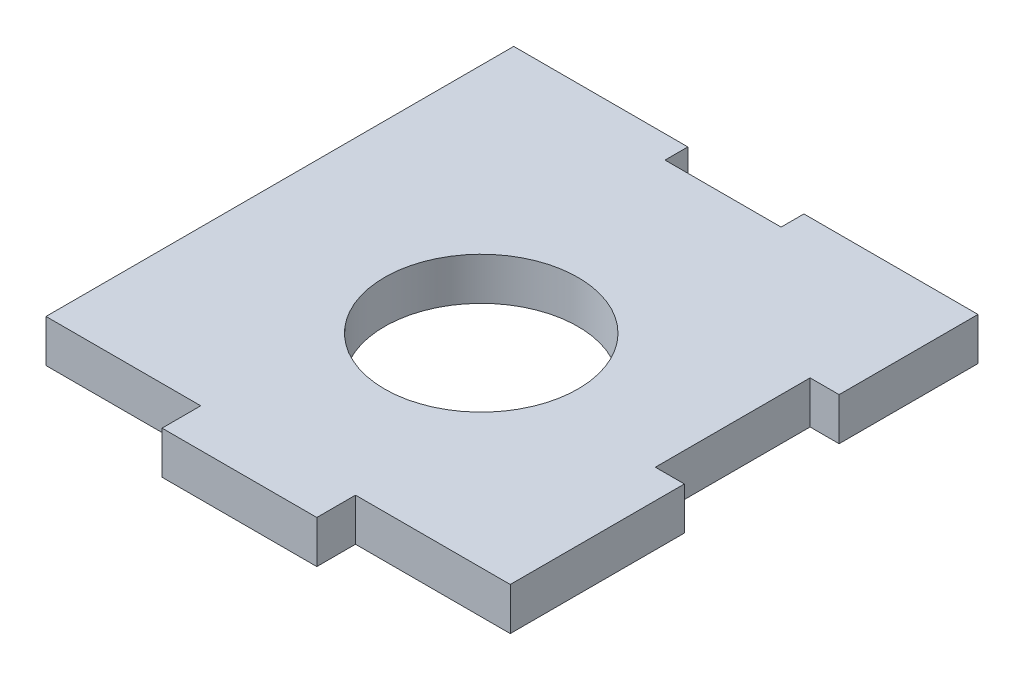
SolidWorks part; units mm, degrees
material "cardboard"
ref_plane "Front Plane" through (0, 0, 0) normal (0, 0, 1) x (1, 0, 0)
ref_plane "Top Plane" through (0, 0, 0) normal (0, 1, 0) x (1, 0, 0)
ref_plane "Right Plane" through (0, 0, 0) normal (1, 0, 0) x (0, 0, -1)
sketch "Sketch1" plane through (0, 0, 0) normal (0, 1, 0) x (1, 0, 0)
  line L0 (77.2136, 11.3295) -> (70.3635, 7.3746)
  line L1 (102.7136, -12.6705) -> (109.5638, -8.7155)
  line L2 (117.8635, 7.3746) -> (109.5638, 7.3746)
  line L3 (117.8635, -8.7155) -> (109.5638, -8.7155)
  line L4 (70.3635, 7.3746) -> (62.0638, 7.3746)
  line L5 (124.7136, 11.3295) -> (117.8635, 7.3746)
  line L6 (124.7136, -12.6705) -> (117.8635, -8.7155)
  line L7 (102.7136, 11.3295) -> (109.5638, 7.3746)
  line L8 (124.7136, 11.3295) -> (137.4636, 11.3295)
  line L9 (124.7136, -12.6705) -> (161.4636, -12.6705)
  line L10 (55.2136, 11.3295) -> (62.0638, 7.3746)
  line L11 (55.2136, -12.6705) -> (62.0638, -8.7155)
  line L12 (77.2136, -12.6705) -> (70.3635, -8.7155)
  line L13 (70.3635, -8.7155) -> (62.0638, -8.7155)
  line L14 (77.2136, 11.3295) -> (102.7136, 11.3295)
  line L15 (77.2136, -12.6705) -> (102.7136, -12.6705)
  line L16 (-12.5364, 77.0795) -> (-8.5815, 70.2294)
  line L17 (11.4636, 102.5795) -> (7.5087, 109.4297)
  line L18 (-8.5815, 117.7294) -> (-8.5815, 109.4297)
  line L19 (7.5087, 117.7294) -> (7.5087, 109.4297)
  line L20 (-8.5815, 70.2294) -> (-8.5815, 61.9297)
  line L21 (-12.5364, 124.5795) -> (-8.5815, 117.7294)
  line L22 (11.4636, 124.5795) -> (7.5087, 117.7294)
  line L23 (-12.5364, 102.5795) -> (-8.5815, 109.4297)
  line L24 (-12.5364, 124.5795) -> (-12.5364, 137.3295)
  line L25 (11.4636, 124.5795) -> (11.4636, 161.3295)
  line L26 (-12.5364, 55.0795) -> (-8.5815, 61.9297)
  line L27 (11.4636, 55.0795) -> (7.5087, 61.9297)
  line L28 (11.4636, 77.0795) -> (7.5087, 70.2294)
  line L29 (7.5087, 70.2294) -> (7.5087, 61.9297)
  line L30 (-12.5364, 77.0795) -> (-12.5364, 102.5795)
  line L31 (11.4636, 77.0795) -> (11.4636, 102.5795)
  line L32 (89.9636, 36.3295) -> (89.9636, 16.3295)
  line L33 (88.9636, 36.3295) -> (88.9636, 30.3295)
  line L34 (36.4636, 11.3295) -> (42.4636, 11.3295)
  line L35 (88.9636, 30.3295) -> (90.9636, 30.3295)
  line L36 (41.2136, 11.3295) -> (41.2136, 9.3295)
  line L37 (42.4636, 11.3295) -> (55.2136, 11.3295)
  line L38 (137.4636, 11.3295) -> (137.4636, -12.6705)
  line L39 (137.4636, 11.3295) -> (161.4636, 11.3295)
  line L40 (161.4636, 11.3295) -> (161.4636, 9.3295)
  line L41 (-29.0328, 13.6838) -> (-0.5364, -14.8126)
  line L42 (-29.0328, 13.6838) -> (-14.8907, 27.8259)
  line L43 (-0.5364, -14.8126) -> (13.6058, -0.6705)
  line L44 (-14.8907, 27.8259) -> (13.6058, -0.6705)
  line L45 (137.4636, 11.3295) -> (137.4636, 36.3295)
  line L46 (39.4636, 36.3295) -> (161.4636, 36.3295)
  line L47 (161.4636, 36.3295) -> (161.4636, 11.3295)
  line L48 (90.9636, 30.3295) -> (90.9636, 22.3295)
  line L49 (137.4636, 36.3295) -> (137.4636, 60.3295)
  line L50 (137.4636, 60.3295) -> (146.4636, 60.3295)
  line L51 (42.4636, 36.3295) -> (42.4636, 16.3295)
  line L52 (161.4636, 60.3295) -> (161.4636, 50.6515)
  line L53 (146.4636, 60.3295) -> (146.4636, 62.5295)
  line L54 (152.4636, 62.5295) -> (152.4636, 60.3295)
  line L55 (152.4636, 60.3295) -> (161.4636, 60.3295)
  line L56 (-59.5364, 137.3295) -> (-59.5364, 112.8295)
  line L57 (-39.5364, 112.8295) -> (-39.5364, 137.3295)
  line L58 (90.9636, 22.3295) -> (88.9636, 22.3295)
  line L59 (137.4636, -12.6705) -> (137.4636, -37.6705)
  line L60 (146.4636, -37.6705) -> (152.4636, -37.6705)
  line L61 (161.4636, -37.6705) -> (161.4636, -12.6705)
  line L62 (42.4636, -37.6705) -> (42.4636, -17.6705)
  line L63 (137.4636, -37.6705) -> (137.4636, -38.8505)
  line L64 (152.4636, -38.8505) -> (161.4636, -38.8505)
  line L65 (161.4636, -38.8505) -> (161.4636, -37.6705)
  line L66 (146.4636, -38.8505) -> (146.4636, -37.6705)
  line L67 (152.4636, -38.8505) -> (152.4636, -37.6705)
  line L68 (-38.7164, -138.6705) -> (-38.7164, -147.6705)
  line L69 (88.9636, 22.3295) -> (88.9636, 16.3295)
  line L70 (88.9636, 11.3295) -> (88.9636, 3.3295)
  line L71 (42.4636, -12.6705) -> (55.2136, -12.6705)
  line L72 (36.4636, -12.6705) -> (42.4636, -12.6705)
  line L73 (89.9374, 11.3295) -> (89.9374, -12.6705)
  line L74 (88.9636, 3.3295) -> (90.9636, 3.3295)
  line L75 (90.9636, 3.3295) -> (90.9636, -4.6705)
  line L76 (90.9636, -4.6705) -> (88.9636, -4.6705)
  line L77 (135.4636, 11.3295) -> (135.4636, 3.3295)
  line L78 (135.4636, 3.3295) -> (139.4636, 3.3295)
  line L79 (37.6436, 161.3295) -> (37.6436, 152.3295)
  line L80 (37.4636, 34.3295) -> (37.4636, 18.3295)
  line L81 (39.4636, 16.3295) -> (137.4636, 16.3295)
  line L82 (41.2136, 23.3295) -> (41.2136, 16.3295)
  line L83 (42.4636, 29.3295) -> (39.4636, 29.3295)
  line L84 (39.4636, 29.3295) -> (39.4636, 23.3295)
  line L85 (43.7136, 5.3295) -> (41.2136, 5.3295)
  line L86 (5.4636, -42.4205) -> (5.4636, -40.4205)
  line L87 (41.2136, -6.6705) -> (43.7136, -6.6705)
  line L88 (43.7136, 5.3295) -> (43.7136, -6.6705)
  line L89 (42.4636, 11.3295) -> (42.4636, 5.3295)
  line L90 (41.2136, 9.3295) -> (43.7136, 9.3295)
  line L91 (43.7136, 9.3295) -> (43.7136, 7.3295)
  line L92 (43.7136, 7.3295) -> (41.2136, 7.3295)
  line L93 (41.2136, 7.3295) -> (41.2136, 5.3295)
  line L94 (41.2136, -8.6705) -> (41.2136, -6.6705)
  line L95 (43.7136, -8.6705) -> (41.2136, -8.6705)
  line L96 (43.7136, -10.6705) -> (43.7136, -8.6705)
  line L97 (41.2136, -10.6705) -> (43.7136, -10.6705)
  line L98 (41.2136, -12.6705) -> (41.2136, -10.6705)
  line L99 (139.4636, 3.3295) -> (139.4636, -4.6705)
  line L100 (139.4636, -4.6705) -> (135.4636, -4.6705)
  line L101 (135.4636, -4.6705) -> (135.4636, -12.6705)
  line L102 (137.4636, 13.3295) -> (145.4636, 13.3295)
  line L103 (145.4636, 13.3295) -> (145.4636, 9.3295)
  line L104 (145.4636, 9.3295) -> (153.4636, 9.3295)
  line L105 (153.4636, 9.3295) -> (153.4636, 13.3295)
  line L106 (153.4636, 13.3295) -> (161.4636, 13.3295)
  line L107 (135.9636, 36.3295) -> (135.9636, 30.3295)
  line L108 (135.9636, 30.3295) -> (138.9636, 30.3295)
  line L109 (138.9636, 30.3295) -> (138.9636, 22.3295)
  line L110 (138.9636, 22.3295) -> (135.9636, 22.3295)
  line L111 (135.9636, 22.3295) -> (135.9636, 16.3295)
  line L112 (88.9636, -4.6705) -> (88.9636, -12.6705)
  line L113 (88.9636, -23.6705) -> (88.9636, -17.6705)
  line L114 (89.9636, -37.6705) -> (89.9636, -17.6705)
  line L115 (90.9636, -23.6705) -> (88.9636, -23.6705)
  line L116 (90.9636, -31.6705) -> (90.9636, -23.6705)
  line L117 (153.4636, -14.6705) -> (161.4636, -14.6705)
  line L118 (153.4636, -10.6705) -> (153.4636, -14.6705)
  line L119 (145.4636, -10.6705) -> (153.4636, -10.6705)
  line L120 (145.4636, -14.6705) -> (145.4636, -10.6705)
  line L121 (137.4636, -14.6705) -> (145.4636, -14.6705)
  line L122 (135.9636, -23.6705) -> (135.9636, -17.6705)
  line L123 (138.9636, -23.6705) -> (135.9636, -23.6705)
  line L124 (41.2136, 36.3295) -> (41.2136, 29.3295)
  line L125 (42.4636, 23.3295) -> (39.4636, 23.3295)
  line L126 (137.4636, -37.6705) -> (39.4636, -37.6705)
  line L127 (37.4636, -35.6705) -> (37.4636, -19.6705)
  line L128 (39.4636, -17.6705) -> (137.4636, -17.6705)
  line L129 (138.9636, -31.6705) -> (138.9636, -23.6705)
  line L130 (135.9636, -31.6705) -> (138.9636, -31.6705)
  line L131 (135.9636, -37.6705) -> (135.9636, -31.6705)
  line L132 (88.9636, -31.6705) -> (90.9636, -31.6705)
  line L133 (88.9636, -37.6705) -> (88.9636, -31.6705)
  line L134 (137.4636, 38.3295) -> (145.4636, 38.3295)
  line L135 (145.4636, 38.3295) -> (145.4636, 34.3295)
  line L136 (145.4636, 34.3295) -> (153.4636, 34.3295)
  line L137 (153.4636, 34.3295) -> (153.4636, 38.3295)
  line L138 (153.4636, 38.3295) -> (161.4636, 38.3295)
  line L139 (-45.0364, 133.0795) -> (-45.0364, 117.0795)
  line L140 (-56.5364, 133.0795) -> (-54.0364, 133.0795)
  line L141 (-56.5364, 133.0795) -> (-56.5364, 117.0795)
  line L142 (-56.5364, 117.0795) -> (-54.0364, 117.0795)
  line L143 (-54.0364, 133.0795) -> (-54.0364, 117.0795)
  line L144 (41.2136, -24.6705) -> (41.2136, -17.6705)
  line L145 (42.4636, -24.6705) -> (39.4636, -24.6705)
  line L146 (39.4636, -30.6705) -> (39.4636, -24.6705)
  line L147 (42.4636, -30.6705) -> (39.4636, -30.6705)
  line L148 (41.2136, -37.6705) -> (41.2136, -30.6705)
  line L149 (196.4636, 4.3295) -> (196.4636, -5.6705)
  line L150 (191.4636, 9.3295) -> (161.4636, 9.3295)
  line L151 (191.4636, -10.6705) -> (161.4636, -10.6705)
  line L152 (191.4636, 9.3295) -> (196.4636, 4.3295)
  line L153 (196.4636, -5.6705) -> (191.4636, -10.6705)
  line L154 (161.4636, -10.6705) -> (161.4636, -12.6705)
  line L155 (137.4636, 62.5295) -> (146.4636, 62.5295)
  line L156 (137.4636, 62.5295) -> (137.4636, 64.5295)
  line L157 (137.4636, 64.5295) -> (161.4636, 64.5295)
  line L158 (161.4636, 64.5295) -> (161.4636, 62.5295)
  line L159 (152.4636, 62.5295) -> (161.4636, 62.5295)
  line L160 (-42.5364, 117.0795) -> (-45.0364, 117.0795)
  line L161 (-42.5364, 133.0795) -> (-42.5364, 117.0795)
  line L162 (-42.5364, 133.0795) -> (-45.0364, 133.0795)
  line L163 (154.8636, 50.6515) -> (161.4636, 50.6515)
  line L164 (154.8636, 50.6515) -> (154.8636, 46.1515)
  line L165 (154.8636, 46.1515) -> (161.4636, 46.1515)
  line L166 (161.4636, 46.1515) -> (161.4636, 36.3295)
  line L167 (11.4636, -78.4205) -> (7.5087, -71.5703)
  line L168 (-12.5364, -103.9205) -> (-8.5815, -110.7706)
  line L169 (7.5087, -119.0703) -> (7.5087, -110.7706)
  line L170 (11.4636, -37.6705) -> (11.4636, -43.6705)
  line L171 (11.4636, -42.4205) -> (9.4636, -42.4205)
  line L172 (11.4636, -43.6705) -> (11.4636, -56.4205)
  line L173 (-8.5815, -119.0703) -> (-8.5815, -110.7706)
  line L174 (7.5087, -71.5703) -> (7.5087, -63.2706)
  line L175 (11.4636, -125.9205) -> (7.5087, -119.0703)
  line L176 (-12.5364, -125.9205) -> (-8.5815, -119.0703)
  line L177 (11.4636, -103.9205) -> (7.5087, -110.7706)
  line L178 (11.4636, -125.9205) -> (11.4636, -138.6705)
  line L179 (-12.5364, -125.9205) -> (-12.5364, -162.6705)
  line L180 (11.4636, -56.4205) -> (7.5087, -63.2706)
  line L181 (-12.5364, -56.4205) -> (-8.5815, -63.2706)
  line L182 (36.4636, -43.6705) -> (16.4636, -43.6705)
  line L183 (-12.5364, -78.4205) -> (-8.5815, -71.5703)
  line L184 (-8.5815, -71.5703) -> (-8.5815, -63.2706)
  line L185 (11.4636, -78.4205) -> (11.4636, -103.9205)
  line L186 (-12.5364, -78.4205) -> (-12.5364, -103.9205)
  line L187 (36.4636, -91.1705) -> (16.4636, -91.1705)
  line L188 (36.4636, -90.1705) -> (30.4636, -90.1705)
  line L189 (30.4636, -90.1705) -> (30.4636, -92.1705)
  line L190 (11.4636, -138.6705) -> (-12.5364, -138.6705)
  line L191 (11.4636, -138.6705) -> (11.4636, -162.6705)
  line L192 (11.4636, -162.6705) -> (9.4636, -162.6705)
  line L193 (11.4636, -138.6705) -> (36.4636, -138.6705)
  line L194 (36.4636, -40.6705) -> (36.4636, -162.6705)
  line L195 (-37.5364, -43.6705) -> (-17.5364, -43.6705)
  line L196 (36.4636, -162.6705) -> (11.4636, -162.6705)
  line L197 (30.4636, -92.1705) -> (22.4636, -92.1705)
  line L198 (36.4636, -138.6705) -> (60.4636, -138.6705)
  line L199 (60.4636, -138.6705) -> (60.4636, -147.6705)
  line L200 (60.4636, -162.6705) -> (50.7856, -162.6705)
  line L201 (60.4636, -147.6705) -> (62.6636, -147.6705)
  line L202 (62.6636, -153.6705) -> (60.4636, -153.6705)
  line L203 (60.4636, -153.6705) -> (60.4636, -162.6705)
  line L204 (-12.5364, -43.6705) -> (-12.5364, -56.4205)
  line L205 (-12.5364, -37.6705) -> (-12.5364, -43.6705)
  line L206 (22.4636, -92.1705) -> (22.4636, -90.1705)
  line L207 (-12.5364, -138.6705) -> (-37.5364, -138.6705)
  line L208 (-37.5364, -147.6705) -> (-37.5364, -153.6705)
  line L209 (37.6436, 146.3295) -> (37.6436, 137.3295)
  line L210 (34.4636, -38.6705) -> (18.4636, -38.6705)
  line L211 (16.4636, -40.6705) -> (16.4636, -138.6705)
  line L212 (23.4636, -42.4205) -> (16.4636, -42.4205)
  line L213 (29.4636, -43.6705) -> (29.4636, -40.6705)
  line L214 (29.4636, -40.6705) -> (23.4636, -40.6705)
  line L215 (5.4636, -44.9205) -> (5.4636, -42.4205)
  line L216 (-37.5364, -162.6705) -> (-12.5364, -162.6705)
  line L217 (-6.5364, -42.4205) -> (-6.5364, -44.9205)
  line L218 (5.4636, -44.9205) -> (-6.5364, -44.9205)
  line L219 (11.4636, -43.6705) -> (5.4636, -43.6705)
  line L220 (9.4636, -42.4205) -> (9.4636, -44.9205)
  line L221 (9.4636, -44.9205) -> (7.4636, -44.9205)
  line L222 (7.4636, -44.9205) -> (7.4636, -42.4205)
  line L223 (7.4636, -42.4205) -> (5.4636, -42.4205)
  line L224 (-8.5364, -42.4205) -> (-6.5364, -42.4205)
  line L225 (-8.5364, -44.9205) -> (-8.5364, -42.4205)
  line L226 (-10.5364, -44.9205) -> (-8.5364, -44.9205)
  line L227 (-10.5364, -42.4205) -> (-10.5364, -44.9205)
  line L228 (-12.5364, -42.4205) -> (-10.5364, -42.4205)
  line L229 (-37.5364, -138.6705) -> (-38.7164, -138.6705)
  line L230 (-38.7164, -153.6705) -> (-38.7164, -162.6705)
  line L231 (-38.7164, -162.6705) -> (-37.5364, -162.6705)
  line L232 (-38.7164, -147.6705) -> (-37.5364, -147.6705)
  line L233 (-38.7164, -153.6705) -> (-37.5364, -153.6705)
  line L234 (-162.5364, 37.5095) -> (-153.5364, 37.5095)
  line L235 (22.4636, -90.1705) -> (16.4636, -90.1705)
  line L236 (11.4636, -90.1705) -> (3.4636, -90.1705)
  line L237 (11.4636, -91.1443) -> (-12.5364, -91.1443)
  line L238 (3.4636, -90.1705) -> (3.4636, -92.1705)
  line L239 (3.4636, -92.1705) -> (-4.5364, -92.1705)
  line L240 (-4.5364, -92.1705) -> (-4.5364, -90.1705)
  line L241 (11.4636, -136.6705) -> (3.4636, -136.6705)
  line L242 (3.4636, -136.6705) -> (3.4636, -140.6705)
  line L243 (3.4636, -140.6705) -> (-4.5364, -140.6705)
  line L244 (-4.5364, -140.6705) -> (-4.5364, -136.6705)
  line L245 (-4.5364, -136.6705) -> (-12.5364, -136.6705)
  line L246 (13.4636, -138.6705) -> (13.4636, -146.6705)
  line L247 (13.4636, -146.6705) -> (9.4636, -146.6705)
  line L248 (9.4636, -146.6705) -> (9.4636, -154.6705)
  line L249 (9.4636, -154.6705) -> (13.4636, -154.6705)
  line L250 (13.4636, -154.6705) -> (13.4636, -162.6705)
  line L251 (36.4636, -137.1705) -> (30.4636, -137.1705)
  line L252 (30.4636, -137.1705) -> (30.4636, -140.1705)
  line L253 (30.4636, -140.1705) -> (22.4636, -140.1705)
  line L254 (36.4636, -42.4205) -> (29.4636, -42.4205)
  line L255 (23.4636, -43.6705) -> (23.4636, -40.6705)
  line L256 (-37.5364, -138.6705) -> (-37.5364, -40.6705)
  line L257 (-35.5364, -38.6705) -> (-19.5364, -38.6705)
  line L258 (-17.5364, -40.6705) -> (-17.5364, -138.6705)
  line L259 (22.4636, -140.1705) -> (22.4636, -137.1705)
  line L260 (22.4636, -137.1705) -> (16.4636, -137.1705)
  line L261 (-4.5364, -90.1705) -> (-12.5364, -90.1705)
  line L262 (-23.5364, -90.1705) -> (-17.5364, -90.1705)
  line L263 (-37.5364, -91.1705) -> (-17.5364, -91.1705)
  line L264 (-23.5364, -92.1705) -> (-23.5364, -90.1705)
  line L265 (-31.5364, -92.1705) -> (-23.5364, -92.1705)
  line L266 (-14.5364, -154.6705) -> (-14.5364, -162.6705)
  line L267 (-10.5364, -154.6705) -> (-14.5364, -154.6705)
  line L268 (-10.5364, -146.6705) -> (-10.5364, -154.6705)
  line L269 (-14.5364, -146.6705) -> (-10.5364, -146.6705)
  line L270 (-14.5364, -138.6705) -> (-14.5364, -146.6705)
  line L271 (-23.5364, -137.1705) -> (-17.5364, -137.1705)
  line L272 (-23.5364, -140.1705) -> (-23.5364, -137.1705)
  line L273 (-31.5364, -140.1705) -> (-23.5364, -140.1705)
  line L274 (-24.5364, -42.4205) -> (-17.5364, -42.4205)
  line L275 (-24.5364, -43.6705) -> (-24.5364, -40.6705)
  line L276 (-30.5364, -40.6705) -> (-24.5364, -40.6705)
  line L277 (-30.5364, -43.6705) -> (-30.5364, -40.6705)
  line L278 (-37.5364, -42.4205) -> (-30.5364, -42.4205)
  line L279 (-31.5364, -137.1705) -> (-31.5364, -140.1705)
  line L280 (-37.5364, -137.1705) -> (-31.5364, -137.1705)
  line L281 (-31.5364, -90.1705) -> (-31.5364, -92.1705)
  line L282 (-37.5364, -90.1705) -> (-31.5364, -90.1705)
  line L283 (38.4636, -138.6705) -> (38.4636, -146.6705)
  line L284 (38.4636, -146.6705) -> (34.4636, -146.6705)
  line L285 (34.4636, -146.6705) -> (34.4636, -154.6705)
  line L286 (34.4636, -154.6705) -> (38.4636, -154.6705)
  line L287 (38.4636, -154.6705) -> (38.4636, -162.6705)
  line L288 (4.4636, -197.6705) -> (-5.5364, -197.6705)
  line L289 (9.4636, -192.6705) -> (9.4636, -162.6705)
  line L290 (-10.5364, -192.6705) -> (-10.5364, -162.6705)
  line L291 (9.4636, -192.6705) -> (4.4636, -197.6705)
  line L292 (-5.5364, -197.6705) -> (-10.5364, -192.6705)
  line L293 (-10.5364, -162.6705) -> (-12.5364, -162.6705)
  line L294 (62.6636, -138.6705) -> (62.6636, -147.6705)
  line L295 (62.6636, -138.6705) -> (64.6636, -138.6705)
  line L296 (64.6636, -138.6705) -> (64.6636, -162.6705)
  line L297 (64.6636, -162.6705) -> (62.6636, -162.6705)
  line L298 (62.6636, -153.6705) -> (62.6636, -162.6705)
  line L299 (-37.5364, -12.6705) -> (-43.5364, -12.6705)
  line L300 (-42.2864, -12.6705) -> (-42.2864, -10.6705)
  line L301 (-43.5364, -12.6705) -> (-56.2864, -12.6705)
  line L302 (50.7856, -156.0705) -> (50.7856, -162.6705)
  line L303 (50.7856, -156.0705) -> (46.2856, -156.0705)
  line L304 (-43.5364, -37.6705) -> (-43.5364, -17.6705)
  line L305 (46.2856, -156.0705) -> (46.2856, -162.6705)
  line L306 (46.2856, -162.6705) -> (36.4636, -162.6705)
  line L307 (-78.2864, -12.6705) -> (-71.4362, -8.7155)
  line L308 (-103.7864, 11.3295) -> (-110.6365, 7.3746)
  line L309 (-118.9362, -8.7155) -> (-110.6365, -8.7155)
  line L310 (-118.9362, 7.3746) -> (-110.6365, 7.3746)
  line L311 (-71.4362, -8.7155) -> (-63.1365, -8.7155)
  line L312 (-125.7864, -12.6705) -> (-118.9362, -8.7155)
  line L313 (-125.7864, 11.3295) -> (-118.9362, 7.3746)
  line L314 (-103.7864, -12.6705) -> (-110.6365, -8.7155)
  line L315 (-125.7864, -12.6705) -> (-138.5364, -12.6705)
  line L316 (-43.5364, 36.3295) -> (-43.5364, 16.3295)
  line L317 (-125.7864, 11.3295) -> (-162.5364, 11.3295)
  line L318 (-56.2864, -12.6705) -> (-63.1365, -8.7155)
  line L319 (-56.2864, 11.3295) -> (-63.1365, 7.3746)
  line L320 (-78.2864, 11.3295) -> (-71.4362, 7.3746)
  line L321 (-71.4362, 7.3746) -> (-63.1365, 7.3746)
  line L322 (-78.2864, -12.6705) -> (-103.7864, -12.6705)
  line L323 (-78.2864, 11.3295) -> (-103.7864, 11.3295)
  line L324 (-91.0364, -37.6705) -> (-91.0364, -17.6705)
  line L325 (-43.5364, 11.3295) -> (-56.2864, 11.3295)
  line L326 (-37.5364, 11.3295) -> (-43.5364, 11.3295)
  line L327 (-90.0364, -37.6705) -> (-90.0364, -31.6705)
  line L328 (-90.0364, -31.6705) -> (-92.0364, -31.6705)
  line L329 (-138.5364, -12.6705) -> (-138.5364, 11.3295)
  line L330 (-138.5364, -12.6705) -> (-162.5364, -12.6705)
  line L331 (-162.5364, -12.6705) -> (-162.5364, -10.6705)
  line L332 (-138.5364, -12.6705) -> (-138.5364, -37.6705)
  line L333 (137.4636, -38.8505) -> (146.4636, -38.8505)
  line L334 (-38.5364, -35.6705) -> (-38.5364, -19.6705)
  line L335 (-40.5364, -17.6705) -> (-138.5364, -17.6705)
  line L336 (-42.2864, -24.6705) -> (-42.2864, -17.6705)
  line L337 (-43.5364, -30.6705) -> (-40.5364, -30.6705)
  line L338 (-40.5364, -30.6705) -> (-40.5364, -24.6705)
  line L339 (-44.7864, -6.6705) -> (-42.2864, -6.6705)
  line L340 (-40.5364, -37.6705) -> (-162.5364, -37.6705)
  line L341 (-42.2864, 5.3295) -> (-44.7864, 5.3295)
  line L342 (-44.7864, -6.6705) -> (-44.7864, 5.3295)
  line L343 (-43.5364, -12.6705) -> (-43.5364, -6.6705)
  line L344 (-42.2864, -10.6705) -> (-44.7864, -10.6705)
  line L345 (-44.7864, -10.6705) -> (-44.7864, -8.6705)
  line L346 (-44.7864, -8.6705) -> (-42.2864, -8.6705)
  line L347 (-42.2864, -8.6705) -> (-42.2864, -6.6705)
  line L348 (-42.2864, 7.3295) -> (-42.2864, 5.3295)
  line L349 (-44.7864, 7.3295) -> (-42.2864, 7.3295)
  line L350 (-44.7864, 9.3295) -> (-44.7864, 7.3295)
  line L351 (-42.2864, 9.3295) -> (-44.7864, 9.3295)
  line L352 (-42.2864, 11.3295) -> (-42.2864, 9.3295)
  line L353 (-162.5364, -37.6705) -> (-162.5364, -12.6705)
  line L354 (-92.0364, -31.6705) -> (-92.0364, -23.6705)
  line L355 (-138.5364, -37.6705) -> (-138.5364, -61.6705)
  line L356 (-138.5364, -61.6705) -> (-147.5364, -61.6705)
  line L357 (-162.5364, -61.6705) -> (-162.5364, -51.9925)
  line L358 (-147.5364, -61.6705) -> (-147.5364, -63.8705)
  line L359 (-153.5364, -63.8705) -> (-153.5364, -61.6705)
  line L360 (-153.5364, -61.6705) -> (-162.5364, -61.6705)
  line L361 (-92.0364, -23.6705) -> (-90.0364, -23.6705)
  line L362 (-138.5364, 11.3295) -> (-138.5364, 36.3295)
  line L363 (-147.5364, 36.3295) -> (-153.5364, 36.3295)
  line L364 (-162.5364, 36.3295) -> (-162.5364, 11.3295)
  line L365 (-138.5364, 36.3295) -> (-138.5364, 37.5095)
  line L366 (-162.5364, 37.5095) -> (-162.5364, 36.3295)
  line L367 (-147.5364, 37.5095) -> (-147.5364, 36.3295)
  line L368 (-153.5364, 37.5095) -> (-153.5364, 36.3295)
  line L369 (-147.5364, 37.5095) -> (-138.5364, 37.5095)
  line L370 (-90.0364, -23.6705) -> (-90.0364, -17.6705)
  line L371 (-90.0364, -12.6705) -> (-90.0364, -4.6705)
  line L372 (-91.0102, -12.6705) -> (-91.0102, 11.3295)
  line L373 (-90.0364, -4.6705) -> (-92.0364, -4.6705)
  line L374 (-42.2864, -37.6705) -> (-42.2864, -30.6705)
  line L375 (-43.5364, -24.6705) -> (-40.5364, -24.6705)
  line L376 (-138.5364, 36.3295) -> (-40.5364, 36.3295)
  line L377 (-38.5364, 34.3295) -> (-38.5364, 18.3295)
  line L378 (-40.5364, 16.3295) -> (-138.5364, 16.3295)
  line L379 (-92.0364, -4.6705) -> (-92.0364, 3.3295)
  line L380 (-92.0364, 3.3295) -> (-90.0364, 3.3295)
  line L381 (-136.5364, -12.6705) -> (-136.5364, -4.6705)
  line L382 (-136.5364, -4.6705) -> (-140.5364, -4.6705)
  line L383 (-140.5364, -4.6705) -> (-140.5364, 3.3295)
  line L384 (-140.5364, 3.3295) -> (-136.5364, 3.3295)
  line L385 (-136.5364, 3.3295) -> (-136.5364, 11.3295)
  line L386 (-138.5364, -14.6705) -> (-146.5364, -14.6705)
  line L387 (-146.5364, -14.6705) -> (-146.5364, -10.6705)
  line L388 (-146.5364, -10.6705) -> (-154.5364, -10.6705)
  line L389 (-154.5364, -10.6705) -> (-154.5364, -14.6705)
  line L390 (-154.5364, -14.6705) -> (-162.5364, -14.6705)
  line L391 (-137.0364, -37.6705) -> (-137.0364, -31.6705)
  line L392 (-37.5364, 89.8295) -> (-17.5364, 89.8295)
  line L393 (-37.5364, 88.8295) -> (-31.5364, 88.8295)
  line L394 (-42.2864, 23.3295) -> (-42.2864, 16.3295)
  line L395 (-43.5364, 23.3295) -> (-40.5364, 23.3295)
  line L396 (-40.5364, 29.3295) -> (-40.5364, 23.3295)
  line L397 (-43.5364, 29.3295) -> (-40.5364, 29.3295)
  line L398 (-42.2864, 36.3295) -> (-42.2864, 29.3295)
  line L399 (-137.0364, -31.6705) -> (-140.0364, -31.6705)
  line L400 (-140.0364, -31.6705) -> (-140.0364, -23.6705)
  line L401 (-140.0364, -23.6705) -> (-137.0364, -23.6705)
  line L402 (-137.0364, -23.6705) -> (-137.0364, -17.6705)
  line L403 (-90.0364, 3.3295) -> (-90.0364, 11.3295)
  line L404 (-90.0364, 22.3295) -> (-90.0364, 16.3295)
  line L405 (-91.0364, 36.3295) -> (-91.0364, 16.3295)
  line L406 (-92.0364, 22.3295) -> (-90.0364, 22.3295)
  line L407 (-92.0364, 30.3295) -> (-92.0364, 22.3295)
  line L408 (-154.5364, 13.3295) -> (-162.5364, 13.3295)
  line L409 (-154.5364, 9.3295) -> (-154.5364, 13.3295)
  line L410 (-146.5364, 9.3295) -> (-154.5364, 9.3295)
  line L411 (-146.5364, 13.3295) -> (-146.5364, 9.3295)
  line L412 (-138.5364, 13.3295) -> (-146.5364, 13.3295)
  line L413 (-137.0364, 22.3295) -> (-137.0364, 16.3295)
  line L414 (-140.0364, 22.3295) -> (-137.0364, 22.3295)
  line L415 (-140.0364, 30.3295) -> (-140.0364, 22.3295)
  line L416 (-137.0364, 30.3295) -> (-140.0364, 30.3295)
  line L417 (-137.0364, 36.3295) -> (-137.0364, 30.3295)
  line L418 (-90.0364, 30.3295) -> (-92.0364, 30.3295)
  line L419 (-90.0364, 36.3295) -> (-90.0364, 30.3295)
  line L420 (-138.5364, -39.6705) -> (-146.5364, -39.6705)
  line L421 (-146.5364, -39.6705) -> (-146.5364, -35.6705)
  line L422 (-146.5364, -35.6705) -> (-154.5364, -35.6705)
  line L423 (-154.5364, -35.6705) -> (-154.5364, -39.6705)
  line L424 (-154.5364, -39.6705) -> (-162.5364, -39.6705)
  line L425 (-12.5364, 41.0795) -> (-10.5364, 41.0795)
  line L426 (-31.5364, 88.8295) -> (-31.5364, 90.8295)
  line L427 (-12.5364, 137.3295) -> (11.4636, 137.3295)
  line L428 (-12.5364, 137.3295) -> (-12.5364, 161.3295)
  line L429 (-12.5364, 161.3295) -> (-10.5364, 161.3295)
  line L430 (-12.5364, 137.3295) -> (-37.5364, 137.3295)
  line L431 (-37.5364, 137.3295) -> (-37.5364, 161.3295)
  line L432 (-37.5364, 161.3295) -> (-12.5364, 161.3295)
  line L433 (-37.5364, 137.3295) -> (-37.5364, 42.3295)
  line L434 (-37.5364, 42.3295) -> (-17.5364, 42.3295)
  line L435 (-17.5364, 42.3295) -> (-17.5364, 137.3295)
  line L436 (-31.5364, 90.8295) -> (-23.5364, 90.8295)
  line L437 (-37.5364, 137.3295) -> (-61.5364, 137.3295)
  line L438 (-61.5364, 137.3295) -> (-61.5364, 146.3295)
  line L439 (-61.5364, 161.3295) -> (-51.8584, 161.3295)
  line L440 (-61.5364, 146.3295) -> (-63.7364, 146.3295)
  line L441 (-63.7364, 152.3295) -> (-61.5364, 152.3295)
  line L442 (-61.5364, 152.3295) -> (-61.5364, 161.3295)
  line L443 (-59.5364, 112.8295) -> (-39.5364, 112.8295)
  line L444 (36.4636, 42.3295) -> (16.4636, 42.3295)
  line L445 (-23.5364, 90.8295) -> (-23.5364, 88.8295)
  line L446 (36.4636, 137.3295) -> (36.4636, 42.3295)
  line L447 (16.4636, 42.3295) -> (16.4636, 137.3295)
  line L448 (11.4636, 137.3295) -> (36.4636, 137.3295)
  line L449 (36.4636, 146.3295) -> (36.4636, 152.3295)
  line L450 (36.4636, 161.3295) -> (11.4636, 161.3295)
  line L451 (11.4636, 36.3295) -> (11.4636, 55.0795)
  line L452 (36.4636, 137.3295) -> (37.6436, 137.3295)
  line L453 (37.6436, 161.3295) -> (36.4636, 161.3295)
  line L454 (37.6436, 146.3295) -> (36.4636, 146.3295)
  line L455 (37.6436, 152.3295) -> (36.4636, 152.3295)
  line L456 (-37.5364, 42.3295) -> (-37.5364, 39.3295)
  line L457 (-35.5364, 37.3295) -> (-19.5364, 37.3295)
  line L458 (-17.5364, 39.3295) -> (-17.5364, 42.3295)
  line L459 (34.4636, 37.3295) -> (18.4636, 37.3295)
  line L460 (16.4636, 39.3295) -> (16.4636, 42.3295)
  line L461 (-6.5364, 43.5795) -> (-6.5364, 41.0795)
  line L462 (-23.5364, 88.8295) -> (-17.5364, 88.8295)
  line L463 (5.4636, 41.0795) -> (5.4636, 43.5795)
  line L464 (-6.5364, 43.5795) -> (5.4636, 43.5795)
  line L465 (-12.5364, 42.3295) -> (-6.5364, 42.3295)
  line L466 (-10.5364, 41.0795) -> (-10.5364, 43.5795)
  line L467 (-10.5364, 43.5795) -> (-8.5364, 43.5795)
  line L468 (-8.5364, 43.5795) -> (-8.5364, 41.0795)
  line L469 (-8.5364, 41.0795) -> (-6.5364, 41.0795)
  line L470 (7.4636, 41.0795) -> (5.4636, 41.0795)
  line L471 (7.4636, 43.5795) -> (7.4636, 41.0795)
  line L472 (9.4636, 43.5795) -> (7.4636, 43.5795)
  line L473 (9.4636, 41.0795) -> (9.4636, 43.5795)
  line L474 (11.4636, 41.0795) -> (9.4636, 41.0795)
  line L475 (-12.5364, 88.8295) -> (-4.5364, 88.8295)
  line L476 (-12.5364, 89.8033) -> (11.4636, 89.8033)
  line L477 (-4.5364, 88.8295) -> (-4.5364, 90.8295)
  line L478 (-4.5364, 90.8295) -> (3.4636, 90.8295)
  line L479 (3.4636, 90.8295) -> (3.4636, 88.8295)
  line L480 (-12.5364, 135.3295) -> (-4.5364, 135.3295)
  line L481 (-4.5364, 135.3295) -> (-4.5364, 139.3295)
  line L482 (-4.5364, 139.3295) -> (3.4636, 139.3295)
  line L483 (3.4636, 139.3295) -> (3.4636, 135.3295)
  line L484 (3.4636, 135.3295) -> (11.4636, 135.3295)
  line L485 (-14.5364, 137.3295) -> (-14.5364, 145.3295)
  line L486 (-14.5364, 145.3295) -> (-10.5364, 145.3295)
  line L487 (-10.5364, 145.3295) -> (-10.5364, 153.3295)
  line L488 (-10.5364, 153.3295) -> (-14.5364, 153.3295)
  line L489 (-14.5364, 153.3295) -> (-14.5364, 161.3295)
  line L490 (-37.5364, 135.8295) -> (-31.5364, 135.8295)
  line L491 (-31.5364, 135.8295) -> (-31.5364, 138.8295)
  line L492 (-31.5364, 138.8295) -> (-23.5364, 138.8295)
  line L493 (-23.5364, 138.8295) -> (-23.5364, 135.8295)
  line L494 (-23.5364, 135.8295) -> (-17.5364, 135.8295)
  line L495 (3.4636, 88.8295) -> (11.4636, 88.8295)
  line L496 (22.4636, 88.8295) -> (16.4636, 88.8295)
  line L497 (36.4636, 89.8295) -> (16.4636, 89.8295)
  line L498 (22.4636, 90.8295) -> (22.4636, 88.8295)
  line L499 (30.4636, 90.8295) -> (22.4636, 90.8295)
  line L500 (-37.5364, 41.0795) -> (-30.5364, 41.0795)
  line L501 (29.4636, 39.3295) -> (23.4636, 39.3295)
  line L502 (23.4636, 41.0795) -> (16.4636, 41.0795)
  line L503 (-30.5364, 42.3295) -> (-30.5364, 39.3295)
  line L504 (-24.5364, 41.0795) -> (-17.5364, 41.0795)
  line L505 (13.4636, 153.3295) -> (13.4636, 161.3295)
  line L506 (9.4636, 153.3295) -> (13.4636, 153.3295)
  line L507 (9.4636, 145.3295) -> (9.4636, 153.3295)
  line L508 (13.4636, 145.3295) -> (9.4636, 145.3295)
  line L509 (13.4636, 137.3295) -> (13.4636, 145.3295)
  line L510 (22.4636, 135.8295) -> (16.4636, 135.8295)
  line L511 (22.4636, 138.8295) -> (22.4636, 135.8295)
  line L512 (30.4636, 138.8295) -> (22.4636, 138.8295)
  line L513 (30.4636, 135.8295) -> (30.4636, 138.8295)
  line L514 (36.4636, 135.8295) -> (30.4636, 135.8295)
  line L515 (30.4636, 88.8295) -> (30.4636, 90.8295)
  line L516 (36.4636, 88.8295) -> (30.4636, 88.8295)
  line L517 (11.4636, 36.3295) -> (20.4281, 27.3651)
  line L518 (36.4636, -12.6705) -> (27.4992, -21.6349)
  line L519 (-12.5364, -37.6705) -> (-21.5008, -28.706)
  line L520 (23.4636, 42.3295) -> (23.4636, 39.3295)
  line L521 (-24.5364, 42.3295) -> (-24.5364, 39.3295)
  line L522 (29.4636, 42.3295) -> (29.4636, 39.3295)
  line L523 (36.4636, 41.0795) -> (29.4636, 41.0795)
  line L524 (-39.5364, 137.3295) -> (-39.5364, 145.3295)
  line L525 (-39.5364, 145.3295) -> (-35.5364, 145.3295)
  line L526 (-35.5364, 145.3295) -> (-35.5364, 153.3295)
  line L527 (-35.5364, 153.3295) -> (-39.5364, 153.3295)
  line L528 (-39.5364, 153.3295) -> (-39.5364, 161.3295)
  line L529 (-59.5364, 135.8295) -> (-52.5364, 135.8295)
  line L530 (-52.5364, 135.8295) -> (-52.5364, 138.8295)
  line L531 (-52.5364, 138.8295) -> (-46.5364, 138.8295)
  line L532 (-46.5364, 138.8295) -> (-46.5364, 135.8295)
  line L533 (-46.5364, 135.8295) -> (-39.5364, 135.8295)
  line L534 (-12.5364, 36.3295) -> (-12.5364, 55.0795)
  line L535 (42.4636, -6.6705) -> (42.4636, -12.6705)
  line L536 (5.4636, 42.3295) -> (11.4636, 42.3295)
  line L537 (-43.5364, 5.3295) -> (-43.5364, 11.3295)
  line L538 (-6.5364, -43.6705) -> (-12.5364, -43.6705)
  line L539 (-5.5364, 196.3295) -> (4.4636, 196.3295)
  line L540 (-10.5364, 191.3295) -> (-10.5364, 161.3295)
  line L541 (9.4636, 191.3295) -> (9.4636, 161.3295)
  line L542 (-10.5364, 191.3295) -> (-5.5364, 196.3295)
  line L543 (4.4636, 196.3295) -> (9.4636, 191.3295)
  line L544 (133.2136, 55.3295) -> (117.2136, 55.3295)
  line L545 (133.2136, 55.3295) -> (133.2136, 52.8295)
  line L546 (-197.5364, -5.6705) -> (-197.5364, 4.3295)
  line L547 (-192.5364, -10.6705) -> (-162.5364, -10.6705)
  line L548 (-192.5364, 9.3295) -> (-162.5364, 9.3295)
  line L549 (-192.5364, -10.6705) -> (-197.5364, -5.6705)
  line L550 (-197.5364, 4.3295) -> (-192.5364, 9.3295)
  line L551 (-162.5364, 9.3295) -> (-162.5364, 11.3295)
  line L552 (-138.5364, -63.8705) -> (-147.5364, -63.8705)
  line L553 (-138.5364, -63.8705) -> (-138.5364, -65.8705)
  line L554 (-138.5364, -65.8705) -> (-162.5364, -65.8705)
  line L555 (-162.5364, -65.8705) -> (-162.5364, -63.8705)
  line L556 (9.4636, 161.3295) -> (11.4636, 161.3295)
  line L557 (-153.5364, -63.8705) -> (-162.5364, -63.8705)
  line L558 (133.2136, 52.8295) -> (117.2136, 52.8295)
  line L559 (117.2136, 55.3295) -> (117.2136, 52.8295)
  line L560 (133.2136, 43.8295) -> (117.2136, 43.8295)
  line L561 (133.2136, 41.3295) -> (133.2136, 43.8295)
  line L562 (133.2136, 41.3295) -> (117.2136, 41.3295)
  line L563 (117.2136, 41.3295) -> (117.2136, 43.8295)
  line L564 (135.9636, 58.3295) -> (135.9636, 51.3295)
  line L565 (135.9636, 51.3295) -> (138.9636, 51.3295)
  line L566 (-155.9364, -51.9925) -> (-162.5364, -51.9925)
  line L567 (-155.9364, -51.9925) -> (-155.9364, -47.4925)
  line L568 (-155.9364, -47.4925) -> (-162.5364, -47.4925)
  line L569 (-63.7364, 137.3295) -> (-63.7364, 146.3295)
  line L570 (-63.7364, 137.3295) -> (-65.7364, 137.3295)
  line L571 (-65.7364, 137.3295) -> (-65.7364, 161.3295)
  line L572 (-65.7364, 161.3295) -> (-63.7364, 161.3295)
  line L573 (-63.7364, 152.3295) -> (-63.7364, 161.3295)
  line L574 (-162.5364, -47.4925) -> (-162.5364, -37.6705)
  line L575 (138.9636, 51.3295) -> (138.9636, 45.3295)
  line L576 (-46.8984, 123.1743) -> (-48.0364, 123.1743)
  line L577 (-52.1743, 127.2156) -> (-51.0364, 127.2156)
  line L578 (-52.1743, 127.2156) -> (-52.1743, 123.1743)
  line L579 (-52.1743, 123.1743) -> (-51.0364, 123.1743)
  line L580 (-51.0364, 127.2156) -> (-51.0364, 123.1743)
  line L581 (-48.0364, 127.2156) -> (-48.0364, 123.1743)
  line L582 (-46.8984, 127.2156) -> (-48.0364, 127.2156)
  line L583 (-46.8984, 127.2156) -> (-46.8984, 123.1743)
  line L584 (138.9636, 45.3295) -> (135.9636, 45.3295)
  line L585 (135.9636, 45.3295) -> (135.9636, 38.3295)
  line L586 (112.9636, 38.3295) -> (137.4636, 38.3295)
  line L587 (112.9636, 58.3295) -> (112.9636, 38.3295)
  line L588 (137.4636, 58.3295) -> (112.9636, 58.3295)
  line L589 (55.4636, -134.4205) -> (55.4636, -118.4205)
  line L590 (55.4636, -134.4205) -> (52.9636, -134.4205)
  line L591 (-51.8584, 154.7295) -> (-51.8584, 161.3295)
  line L592 (-51.8584, 154.7295) -> (-47.3584, 154.7295)
  line L593 (-47.3584, 154.7295) -> (-47.3584, 161.3295)
  line L594 (-47.3584, 161.3295) -> (-37.5364, 161.3295)
  line L595 (52.9636, -134.4205) -> (52.9636, -118.4205)
  line L596 (55.4636, -118.4205) -> (52.9636, -118.4205)
  line L597 (-14.4298, 34.4361) -> (-12.5364, 36.3295)
  line L598 (-21.5008, 34.4361) -> (-23.6222, 36.5574)
  line L599 (-35.643, 20.294) -> (-37.7643, 22.4153)
  line L600 (-37.7643, 22.4153) -> (-23.6222, 36.5574)
  line L601 (5.4636, -40.4205) -> (-6.5364, -40.4205)
  line L602 (41.2136, 5.3295) -> (39.2136, 5.3295)
  line L603 (-6.5364, -42.4205) -> (-6.5364, -40.4205)
  line L604 (41.2136, -6.6705) -> (39.2136, -6.6705)
  line L605 (39.2136, 5.3295) -> (39.2136, -6.6705)
  line L606 (-42.2864, -6.6705) -> (-40.2864, -6.6705)
  line L607 (-40.2864, -6.6705) -> (-40.2864, 5.3295)
  line L608 (-42.2864, 5.3295) -> (-40.2864, 5.3295)
  line L609 (-6.5364, 41.0795) -> (-6.5364, 39.0795)
  line L610 (-6.5364, 39.0795) -> (5.4636, 39.0795)
  line L611 (5.4636, 41.0795) -> (5.4636, 39.0795)
  line L612 (-37.5364, 11.3295) -> (-35.643, 13.2229)
  line L613 (-30.5364, 39.3295) -> (-24.5364, 39.3295)
  line L614 (25.3778, -19.5136) -> (18.3068, -26.5847)
  line L615 (18.3068, 25.2437) -> (25.3778, 18.1727)
  line L616 (25.3778, 18.1727) -> (27.4992, 20.294)
  line L617 (43.9636, -134.4205) -> (43.9636, -118.4205)
  line L618 (41.4636, -134.4205) -> (43.9636, -134.4205)
  line L619 (41.4636, -134.4205) -> (41.4636, -118.4205)
  line L620 (41.4636, -118.4205) -> (43.9636, -118.4205)
  line L621 (58.4636, -137.1705) -> (51.4636, -137.1705)
  line L622 (51.4636, -137.1705) -> (51.4636, -140.1705)
  line L623 (51.4636, -140.1705) -> (45.4636, -140.1705)
  line L624 (45.4636, -140.1705) -> (45.4636, -137.1705)
  line L625 (45.4636, -137.1705) -> (38.4636, -137.1705)
  line L626 (38.4636, -114.1705) -> (38.4636, -138.6705)
  line L627 (58.4636, -114.1705) -> (38.4636, -114.1705)
  line L628 (58.4636, -138.6705) -> (58.4636, -114.1705)
  line L629 (-134.2864, -56.6705) -> (-118.2864, -56.6705)
  line L630 (-134.2864, -56.6705) -> (-134.2864, -54.1705)
  line L631 (-134.2864, -54.1705) -> (-118.2864, -54.1705)
  line L632 (-118.2864, -56.6705) -> (-118.2864, -54.1705)
  line L633 (-134.2864, -45.1705) -> (-118.2864, -45.1705)
  line L634 (-134.2864, -42.6705) -> (-134.2864, -45.1705)
  line L635 (-134.2864, -42.6705) -> (-118.2864, -42.6705)
  line L636 (-118.2864, -42.6705) -> (-118.2864, -45.1705)
  line L637 (-137.0364, -59.6705) -> (-137.0364, -52.6705)
  line L638 (-137.0364, -52.6705) -> (-140.0364, -52.6705)
  line L639 (-140.0364, -52.6705) -> (-140.0364, -46.6705)
  line L640 (-140.0364, -46.6705) -> (-137.0364, -46.6705)
  line L641 (-137.0364, -46.6705) -> (-137.0364, -39.6705)
  line L642 (-114.0364, -39.6705) -> (-138.5364, -39.6705)
  line L643 (-114.0364, -59.6705) -> (-114.0364, -39.6705)
  line L644 (-138.5364, -59.6705) -> (-114.0364, -59.6705)
  line L645 (127.3497, 50.9675) -> (123.3084, 50.9675)
  line L646 (127.3497, 50.9675) -> (127.3497, 49.8295)
  line L647 (127.3497, 49.8295) -> (123.3084, 49.8295)
  line L648 (123.3084, 50.9675) -> (123.3084, 49.8295)
  line L649 (127.3497, 46.8295) -> (123.3084, 46.8295)
  line L650 (18.3068, 25.2437) -> (20.4281, 27.3651)
  line L651 (127.3497, 45.6916) -> (127.3497, 46.8295)
  line L652 (127.3497, 45.6916) -> (123.3084, 45.6916)
  line L653 (123.3084, 45.6916) -> (123.3084, 46.8295)
  line L654 (51.1016, -128.5566) -> (51.1016, -124.5153)
  line L655 (51.1016, -128.5566) -> (49.9636, -128.5566)
  line L656 (49.9636, -128.5566) -> (49.9636, -124.5153)
  line L657 (51.1016, -124.5153) -> (49.9636, -124.5153)
  line L658 (46.9636, -128.5566) -> (46.9636, -124.5153)
  line L659 (45.8257, -128.5566) -> (46.9636, -128.5566)
  line L660 (45.8257, -128.5566) -> (45.8257, -124.5153)
  line L661 (45.8257, -124.5153) -> (46.9636, -124.5153)
  line L662 (-128.4225, -52.3084) -> (-124.3812, -52.3084)
  line L663 (-128.4225, -52.3084) -> (-128.4225, -51.1705)
  line L664 (-128.4225, -51.1705) -> (-124.3812, -51.1705)
  line L665 (-124.3812, -52.3084) -> (-124.3812, -51.1705)
  line L666 (-128.4225, -48.1705) -> (-124.3812, -48.1705)
  line L667 (-128.4225, -47.0325) -> (-128.4225, -48.1705)
  line L668 (-128.4225, -47.0325) -> (-124.3812, -47.0325)
  line L669 (-124.3812, -47.0325) -> (-124.3812, -48.1705)
  line L670 (27.4992, 20.294) -> (36.4636, 11.3295)
  line L671 (18.3068, -26.5847) -> (20.4281, -28.706)
  line L672 (25.3778, -19.5136) -> (27.4992, -21.6349)
  line L673 (-19.3795, -26.5847) -> (-26.4506, -19.5136)
  line L674 (-26.4506, -19.5136) -> (-28.5719, -21.6349)
  line L675 (-19.3795, -26.5847) -> (-21.5008, -28.706)
  line L676 (20.4281, -28.706) -> (11.4636, -37.6705)
  line L677 (-28.5719, -21.6349) -> (-37.5364, -12.6705)
  line L678 (36.4636, 42.3295) -> (36.4636, 39.3295)
  circle A0 centre (156.1811, 41.612) radius 1.5
  circle A1 centre (142.7461, 55.047) radius 1.5
  circle A2 centre (155.1205, 53.9864) radius 1.5
  circle A3 centre (143.8068, 42.6727) radius 1.5
  circle A4 centre (149.4636, 48.3295) radius 3.1
  circle A5 centre (149.4636, 23.8295) radius 5
  circle A6 centre (149.4636, -25.1705) radius 5
  circle A7 centre (66.2136, 26.3295) radius 5
  circle A8 centre (113.4642, 26.3295) radius 5
  circle A9 centre (66.2136, -27.6705) radius 5
  circle A10 centre (113.4642, -27.6705) radius 5
  circle A11 centre (149.4636, -0.6705) radius 7
  circle A12 centre (41.7461, -157.388) radius 1.5
  circle A13 centre (55.1811, -143.953) radius 1.5
  circle A14 centre (54.1205, -156.3273) radius 1.5
  circle A15 centre (42.8068, -145.0136) radius 1.5
  circle A16 centre (48.4636, -150.6705) radius 3.1
  circle A17 centre (23.9636, -150.6705) radius 5
  circle A18 centre (-42.8189, 156.047) radius 1.5
  circle A19 centre (-56.2539, 142.612) radius 1.5
  circle A20 centre (-55.1932, 154.9864) radius 1.5
  circle A21 centre (-43.8795, 143.6727) radius 1.5
  circle A22 centre (-49.5364, 149.3295) radius 3.1
  circle A23 centre (-25.0364, -150.6705) radius 5
  circle A24 centre (26.4636, -67.4205) radius 5
  circle A25 centre (26.4636, -114.6711) radius 5
  circle A26 centre (-27.5364, -67.4205) radius 5
  circle A27 centre (-27.5364, -114.6711) radius 5
  circle A28 centre (-0.5364, -150.6705) radius 7
  circle A29 centre (-157.2539, -42.953) radius 1.5
  circle A30 centre (-25.0364, 149.3295) radius 5
  circle A31 centre (23.9636, 149.3295) radius 5
  circle A32 centre (-143.8189, -56.388) radius 1.5
  circle A33 centre (-156.1932, -55.3273) radius 1.5
  circle A34 centre (-144.8795, -44.0136) radius 1.5
  circle A35 centre (-150.5364, -49.6705) radius 3.1
  circle A36 centre (-150.5364, -25.1705) radius 5
  circle A37 centre (-150.5364, 23.8295) radius 5
  circle A38 centre (-67.2864, -27.6705) radius 5
  circle A39 centre (-114.537, -27.6705) radius 5
  circle A40 centre (-67.2864, 26.3295) radius 5
  circle A41 centre (-114.537, 26.3295) radius 5
  circle A42 centre (-150.5364, -0.6705) radius 7
  circle A43 centre (-27.5364, 66.0795) radius 5
  circle A44 centre (-27.5364, 113.3301) radius 5
  circle A45 centre (26.4636, 66.0795) radius 5
  circle A46 centre (26.4636, 113.3301) radius 5
  arc A47 (39.4636, 36.3295) -> (37.4636, 34.3295) centre (39.4636, 34.3295) ccw
  arc A48 (37.4636, 18.3295) -> (39.4636, 16.3295) centre (39.4636, 18.3295) ccw
  arc A49 (-19.5364, 37.3295) -> (-17.5364, 39.3295) centre (-19.5364, 39.3295) ccw
  arc A50 (-37.5364, 39.3295) -> (-35.5364, 37.3295) centre (-35.5364, 39.3295) ccw
  arc A51 (36.4636, 39.3295) -> (34.4636, 37.3295) centre (34.4636, 39.3295) cw
  arc A52 (18.4636, 37.3295) -> (16.4636, 39.3295) centre (18.4636, 39.3295) cw
  arc A53 (39.4636, -37.6705) -> (37.4636, -35.6705) centre (39.4636, -35.6705) cw
  arc A54 (37.4636, -19.6705) -> (39.4636, -17.6705) centre (39.4636, -19.6705) cw
  arc A55 (36.4636, -40.6705) -> (34.4636, -38.6705) centre (34.4636, -40.6705) ccw
  arc A56 (18.4636, -38.6705) -> (16.4636, -40.6705) centre (18.4636, -40.6705) ccw
  arc A57 (-37.5364, -40.6705) -> (-35.5364, -38.6705) centre (-35.5364, -40.6705) cw
  arc A58 (-19.5364, -38.6705) -> (-17.5364, -40.6705) centre (-19.5364, -40.6705) cw
  arc A59 (-40.5364, -37.6705) -> (-38.5364, -35.6705) centre (-40.5364, -35.6705) ccw
  arc A60 (-38.5364, -19.6705) -> (-40.5364, -17.6705) centre (-40.5364, -19.6705) ccw
  arc A61 (-40.5364, 36.3295) -> (-38.5364, 34.3295) centre (-40.5364, 34.3295) cw
  arc A62 (-38.5364, 18.3295) -> (-40.5364, 16.3295) centre (-40.5364, 18.3295) cw
  arc A63 (-14.4298, 34.4361) -> (-21.5008, 34.4361) centre (-17.9653, 37.9717) cw
  arc A64 (-35.643, 20.294) -> (-35.643, 13.2229) centre (-39.1785, 16.7585) cw
  circle A65 centre (-0.5364, 149.3295) radius 7
  point P194 (-0.5364, -0.6705)
  point P589 (-0.5364, -0.6705)
  point P595 (-0.5364, -0.6705)
  point P596 (-0.5364, -0.6705)
  point P601 (-0.5364, -0.6705)
  point P604 (-0.5364, -0.6705)
  point P629 (-0.5364, -0.6705)
  point P660 (-0.5364, -0.6705)
  point P686 (-0.5364, -0.6705)
  point P715 (-0.5364, -0.6705)
  point P716 (-0.5364, -0.6705)
  point P740 (-0.5364, -0.6705)
  point P743 (-0.5364, -0.6705)
  point P783 (-0.5364, -0.6705)
  point P809 (-0.5364, -0.6705)
  point P816 (-0.5364, -0.6705)
  point P829 (-0.5364, -0.6705)
  point P860 (-0.5364, -0.6705)
  point P885 (-0.5364, -0.6705)
  point P890 (-0.5364, -0.6705)
  point P910 (-0.5364, -0.6705)
extrude "Boss-Extrude1" add sketch "Sketch1" along normal blind 2.2 contours L416 L362 L365 L369 L367 L363 L368 L234 L366 L364 L408 L409 L317 L411 L412 L414 L415 A37
